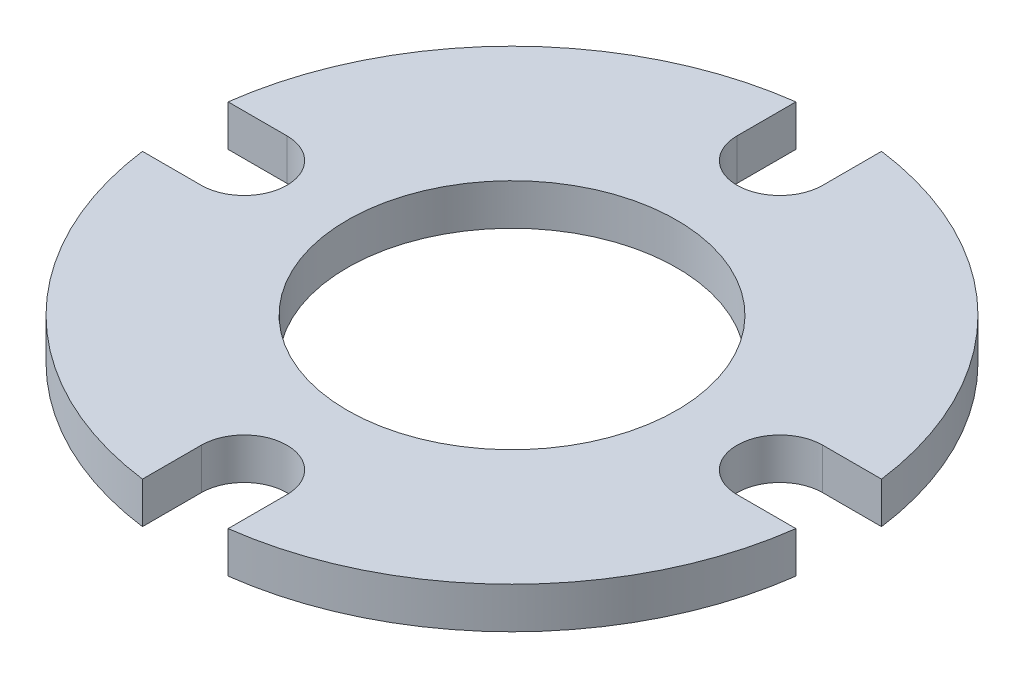
SolidWorks part; units mm, degrees
ref_plane "Front Plane" through (0, 0, 0) normal (0, 0, 1) x (1, 0, 0)
ref_plane "Top Plane" through (0, 0, 0) normal (0, 1, 0) x (1, 0, 0)
ref_plane "Right Plane" through (0, 0, 0) normal (1, 0, 0) x (0, 0, -1)
sketch "Sketch1" plane through (0, 0, 0) normal (0, 1, 0) x (1, 0, 0)
  line L0 (0, 37.3) -> (0, -36.7323) construction
  line L1 (3.302, 20.6502) -> (3.302, 25.1845)
  line L2 (-3.302, 20.6502) -> (-3.302, 25.1845)
  line L3 (20.6502, 3.302) -> (25.1845, 3.302)
  line L4 (20.6502, -3.302) -> (25.1845, -3.302)
  line L5 (3.302, -20.6502) -> (3.302, -25.1845)
  line L6 (-3.302, -20.6502) -> (-3.302, -25.1845)
  line L7 (-20.6502, -3.302) -> (-25.1845, -3.302)
  line L8 (-20.6502, 3.302) -> (-25.1845, 3.302)
  arc A0 (-3.302, 25.1845) -> (-25.1845, 3.302) centre (0, 0) ccw
  circle A1 centre (0, 0) radius 12.7
  arc A2 (-3.302, 20.6502) -> (3.302, 20.6502) centre (0, 20.6502) ccw
  arc A3 (20.6502, 3.302) -> (20.6502, -3.302) centre (20.6502, 0) ccw
  arc A4 (3.302, -20.6502) -> (-3.302, -20.6502) centre (0, -20.6502) ccw
  arc A5 (-20.6502, -3.302) -> (-20.6502, 3.302) centre (-20.6502, 0) ccw
  arc A6 (-25.1845, -3.302) -> (-3.302, -25.1845) centre (0, 0) ccw
  arc A7 (25.1845, 3.302) -> (3.302, 25.1845) centre (0, 0) ccw
  arc A8 (3.302, -25.1845) -> (25.1845, -3.302) centre (0, 0) ccw
  point P29 (0, 0)
  dimension "D1" = 50.8
  dimension "D2" = 25.4
  dimension "D4" = 3.302
  dimension "D3" = 20.6502
  dimension "D5" = 4
extrude "Boss-Extrude1" add sketch "Sketch1" along normal mid plane 3.175
